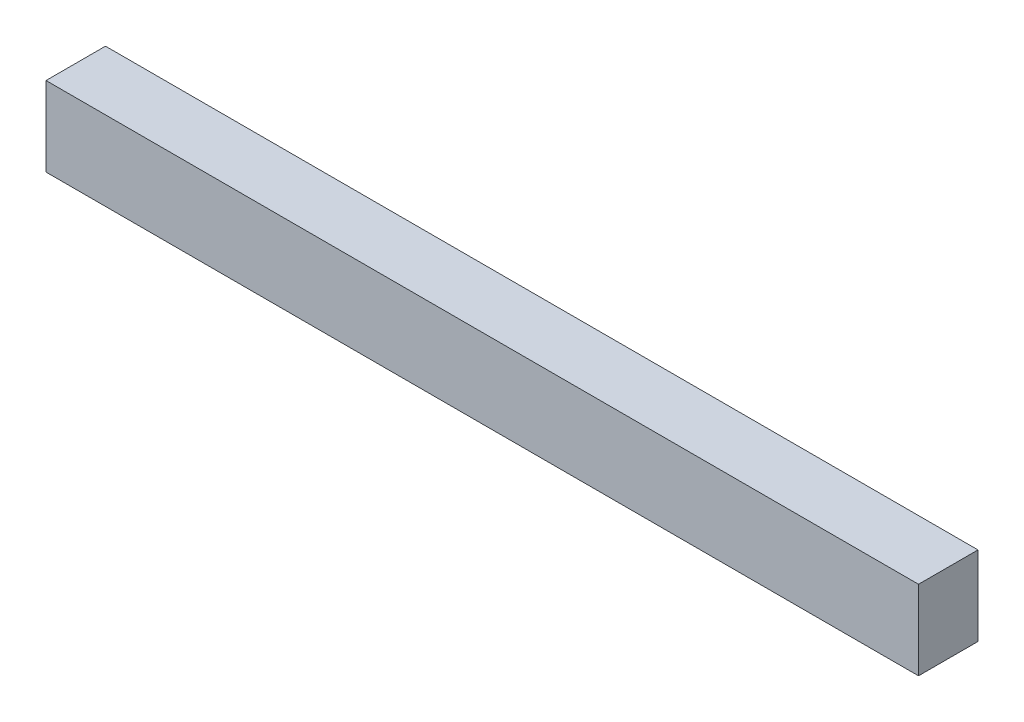
SolidWorks part; units mm, degrees
ref_plane "Plan de face" through (0, 0, 0) normal (0, 0, 1) x (1, 0, 0)
ref_plane "Plan de dessus" through (0, 0, 0) normal (0, 1, 0) x (1, 0, 0)
ref_plane "Plan de droite" through (0, 0, 0) normal (1, 0, 0) x (0, 0, -1)
sketch "Esquisse1" plane through (0, 0, 0) normal (0, 0, 1) x (1, 0, 0)
  line L1 (0, 0) -> (440, 0)
  line L2 (0, 0) -> (0, 40)
  line L3 (0, 40) -> (440, 40)
  line L4 (440, 0) -> (440, 40)
  dimension "D1" = 40
  dimension "D2" = 440
extrude "Boss.-Extru.1" add sketch "Esquisse1" along normal blind 30
